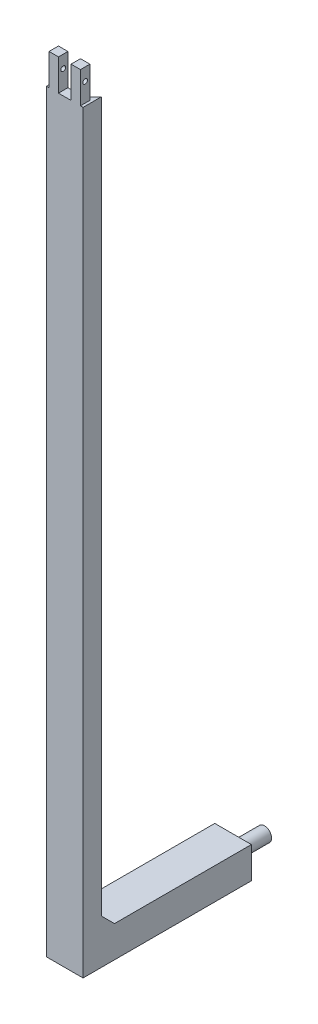
SolidWorks part; units mm, degrees
ref_plane "Front Plane" through (0, 0, 0) normal (0, 0, 1) x (1, 0, 0)
ref_plane "Top Plane" through (0, 0, 0) normal (0, 1, 0) x (1, 0, 0)
ref_plane "Right Plane" through (0, 0, 0) normal (1, 0, 0) x (0, 0, -1)
sketch "Sketch2" plane through (0, 0, 0) normal (0, 0, 1) x (1, 0, 0)
  line L1 (0, 0) -> (-6, 0)
  line L2 (0, 0) -> (0, -240)
  line L3 (0, -240) -> (-6, -240)
  line L4 (-6, 0) -> (-6, -240)
  dimension "D1" = 6
  dimension "D2" = 240
extrude "Boss-Extrude1" add sketch "Sketch2" along normal blind 3
sketch "Sketch4" plane through (0, -240, 0) normal (0, -1, 0) x (-1, 0, 0)
  line L0 (0, 0) -> (-2.8284, 2.8284)
  line L1 (-2.8284, 2.8284) -> (-2.8284, -3)
  line L2 (-2.8284, -3) -> (0, -3)
  line L3 (0, -3) -> (0, 0)
  line L4 (3, 0) -> (3, -3.7119) construction
  line L5 (6, 0) -> (0, 0) construction
  line L6 (8.8284, -3) -> (6, -3)
  line L7 (8.8284, 2.8284) -> (8.8284, -3)
  line L8 (6, 0) -> (8.8284, 2.8284)
  line L9 (6, -3) -> (6, 0)
  dimension "D1" = 135
  dimension "D2" = 4
extrude "Boss-Extrude2" add sketch "Sketch4" against normal up to vertex (240 mm away)
sketch "Sketch5" plane through (0, 0, 0) normal (0, 1, 0) x (1, 0, 0)
  line L0 (2.8284, -3) -> (-8.8284, -3) construction
  line L1 (-8, -3) -> (-5, -3)
  line L2 (-8, -3) -> (-8, 0)
  line L3 (-8, 0) -> (-5, 0)
  line L4 (-5, -3) -> (-5, 0)
  line L5 (-3, 0) -> (-3, -4.0355) construction
  line L6 (0, 0) -> (-6, 0) construction
  line L7 (2, 0) -> (-1, 0)
  line L8 (-1, -3) -> (-1, 0)
  line L9 (2, -3) -> (-1, -3)
  line L10 (2, -3) -> (2, 0)
  dimension "D1" = 3
  dimension "D2" = 2
  dimension "D3" = 0
extrude "Boss-Extrude3" add sketch "Sketch5" along normal blind 10
sketch "Sketch6" plane through (2, 0, 0) normal (1, 0, 0) x (0, 0, -1)
  line L0 (-3, 10) -> (-3, 0) construction
  line L1 (-3, 10) -> (0, 10) construction
  circle A0 centre (-1.5, 6) radius 0.75
  dimension "D1" = 1.5
  dimension "D2" = 1.5
  dimension "D3" = 4
extrude "Cut-Extrude1" cut sketch "Sketch6" against normal blind 40
sketch "Sketch7" plane through (0, 0, 0) normal (0, 0, -1) x (-1, 0, 0)
  line L0 (-2.8284, 0) -> (-2.8284, -240) construction
  line L1 (8.8284, -240) -> (-2.8284, -240)
  line L2 (8.8284, -240) -> (8.8284, -230)
  line L3 (8.8284, -230) -> (-2.8284, -230)
  line L4 (-2.8284, -240) -> (-2.8284, -230)
  dimension "D1" = 10
extrude "Boss-Extrude4" add sketch "Sketch7" along normal blind 50.58
sketch "Sketch8" plane through (0, 0, -50.58) normal (0, 0, -1) x (-1, 0, 0)
  line L0 (-2.8284, -240) -> (8.8284, -240) construction
  line L1 (-2.8284, -230) -> (-2.8284, -240) construction
  circle A0 centre (3, -235) radius 2.25
  point P4 (3, -240)
  point P7 (-2.8284, -235)
  dimension "D1" = 0
  dimension "D2" = 0
  dimension "D3" = 4.5
extrude "Boss-Extrude5" add sketch "Sketch8" along normal blind 10
sketch "Sketch9" plane through (-8.8284, 0, 0) normal (-1, 0, 0) x (0, 0, 1)
  line L0 (-7, -230) -> (0, -230)
  line L1 (-50.58, -230) -> (-2.8284, -230) construction
  line L2 (0, -230) -> (0, -223)
  line L3 (0, -223) -> (-7, -230)
  dimension "D1" = 7
  dimension "D2" = 7
extrude "Boss-Extrude6" add sketch "Sketch9" against normal up to vertex (11.6569 mm away)
